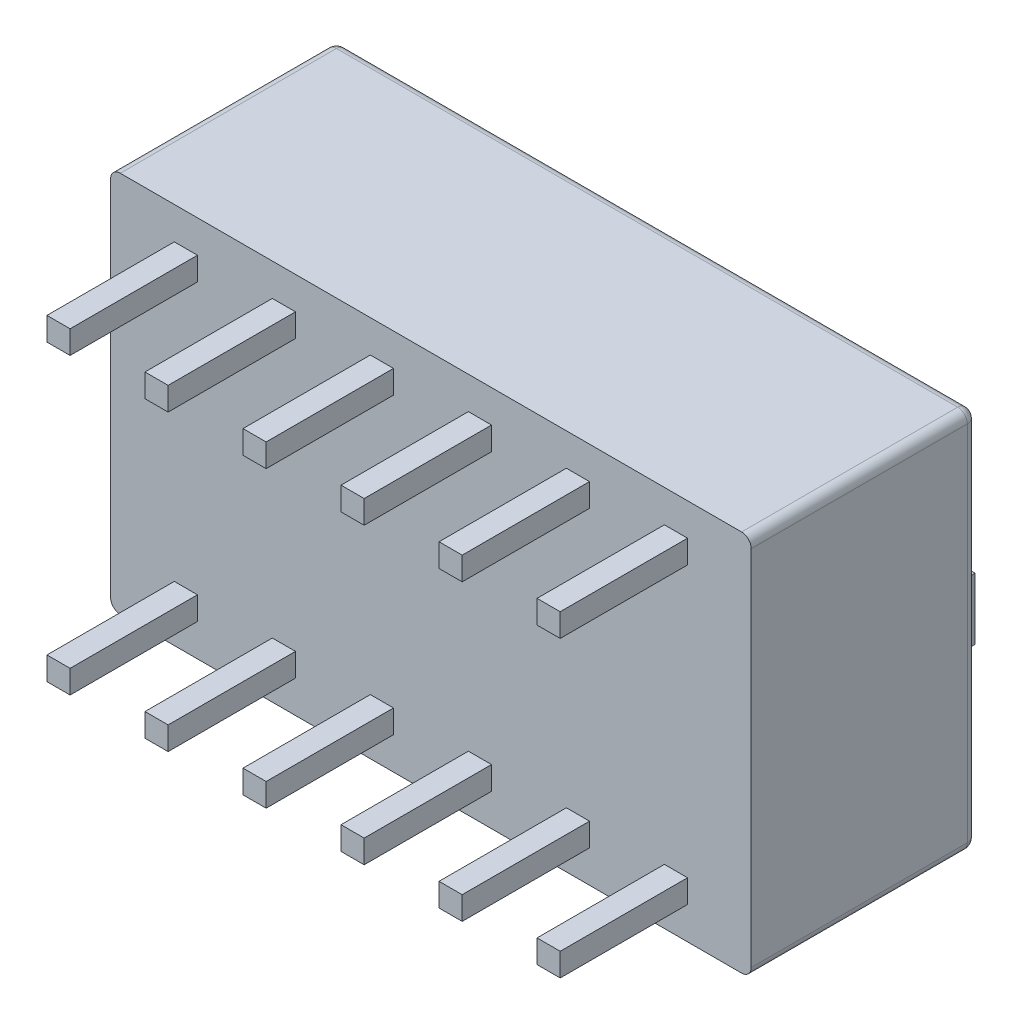
SolidWorks part; units mm, degrees
ref_plane "Ön Düzlem" through (0, 0, 0) normal (0, 0, 1) x (1, 0, 0)
ref_plane "Üst Düzlem" through (0, 0, 0) normal (0, 1, 0) x (1, 0, 0)
ref_plane "Sağ Düzlem" through (0, 0, 0) normal (1, 0, 0) x (0, 0, -1)
sketch "Çizim1" plane through (0, 0, 0) normal (0, 0, 1) x (1, 0, 0)
  line L1 (-8.3, 4.95) -> (8.3, 4.95)
  line L2 (-8.3, 4.95) -> (-8.3, -4.95)
  line L3 (-8.3, -4.95) -> (8.3, -4.95)
  line L4 (8.3, 4.95) -> (8.3, -4.95)
  line L5 (-8.3, 4.95) -> (8.3, -4.95) construction
  line L6 (-8.3, -4.95) -> (8.3, 4.95) construction
  point P0 (0, 0)
extrude "Yükseklik-Ekstrüzyon1" add sketch "Çizim1" along normal blind 5.85
sketch "Çizim2" plane through (0, 0, 0) normal (0, 0, -1) x (-1, 0, 0)
  line L10 (-7.05, 1.6) -> (-5.65, 1.6)
  line L11 (-7.05, 1.6) -> (-7.05, -1.6)
  line L12 (-7.05, -1.6) -> (-5.65, -1.6)
  line L13 (-5.65, 1.6) -> (-5.65, -1.6)
  line L14 (-7.05, 1.6) -> (-5.65, -1.6) construction
  line L15 (-7.05, -1.6) -> (-5.65, 1.6) construction
  line L16 (-4.51, 1.6) -> (-3.11, 1.6)
  line L17 (-4.51, 1.6) -> (-4.51, -1.6)
  line L18 (-4.51, -1.6) -> (-3.11, -1.6)
  line L19 (-3.11, 1.6) -> (-3.11, -1.6)
  line L20 (-4.51, 1.6) -> (-3.11, -1.6) construction
  line L21 (-4.51, -1.6) -> (-3.11, 1.6) construction
  line L22 (-1.97, 1.6) -> (-0.57, 1.6)
  line L23 (-1.97, 1.6) -> (-1.97, -1.6)
  line L24 (-1.97, -1.6) -> (-0.57, -1.6)
  line L25 (-0.57, 1.6) -> (-0.57, -1.6)
  line L26 (-1.97, 1.6) -> (-0.57, -1.6) construction
  line L27 (-1.97, -1.6) -> (-0.57, 1.6) construction
  line L28 (0.57, 1.6) -> (1.97, 1.6)
  line L29 (0.57, 1.6) -> (0.57, -1.6)
  line L30 (0.57, -1.6) -> (1.97, -1.6)
  line L31 (1.97, 1.6) -> (1.97, -1.6)
  line L32 (0.57, 1.6) -> (1.97, -1.6) construction
  line L33 (0.57, -1.6) -> (1.97, 1.6) construction
  line L34 (3.11, 1.6) -> (4.51, 1.6)
  line L35 (3.11, 1.6) -> (3.11, -1.6)
  line L36 (3.11, -1.6) -> (4.51, -1.6)
  line L37 (4.51, 1.6) -> (4.51, -1.6)
  line L38 (3.11, 1.6) -> (4.51, -1.6) construction
  line L39 (3.11, -1.6) -> (4.51, 1.6) construction
  line L40 (7.05, 1.6) -> (5.65, 1.6)
  line L41 (7.05, 1.6) -> (7.05, -1.6)
  line L42 (7.05, -1.6) -> (5.65, -1.6)
  line L43 (5.65, 1.6) -> (5.65, -1.6)
  line L44 (7.05, 1.6) -> (5.65, -1.6) construction
  line L45 (7.05, -1.6) -> (5.65, 1.6) construction
extrude "Kes-Ekstrüzyon1" cut sketch "Çizim2" against normal blind 1
sketch "Çizim3" plane through (0, 0, 1) normal (0, 0, -1) x (-1, 0, 0)
  line L0 (-5.65, -1.6) -> (-5.65, 1.6) construction
  line L1 (-7.05, -1.6) -> (-5.65, -1.6)
  line L2 (-7.05, -1.6) -> (-7.05, 0)
  line L3 (-7.05, 0) -> (-5.65, 0)
  line L4 (-5.65, -1.6) -> (-5.65, 0)
  line L5 (-4.51, 1.6) -> (-4.51, -1.6) construction
  line L6 (-4.51, 0) -> (-3.11, 0)
  line L7 (-4.51, 0) -> (-4.51, -1.6)
  line L8 (-4.51, -1.6) -> (-3.11, -1.6)
  line L9 (-3.11, 0) -> (-3.11, -1.6)
  line L10 (-0.57, -1.6) -> (-0.57, 1.6) construction
  line L11 (-1.97, -1.6) -> (-0.57, -1.6)
  line L12 (-1.97, -1.6) -> (-1.97, 0)
  line L13 (-1.97, 0) -> (-0.57, 0)
  line L14 (-0.57, -1.6) -> (-0.57, 0)
  line L15 (0.57, 1.6) -> (0.57, -1.6) construction
  line L16 (0.57, 0) -> (1.97, 0)
  line L17 (0.57, 0) -> (0.57, -1.6)
  line L18 (0.57, -1.6) -> (1.97, -1.6)
  line L19 (1.97, 0) -> (1.97, -1.6)
  line L20 (4.51, -1.6) -> (4.51, 1.6) construction
  line L21 (3.11, -1.6) -> (4.51, -1.6)
  line L22 (3.11, -1.6) -> (3.11, 0)
  line L23 (3.11, 0) -> (4.51, 0)
  line L24 (4.51, -1.6) -> (4.51, 0)
  line L25 (5.65, 1.6) -> (5.65, -1.6) construction
  line L26 (5.65, 0) -> (7.05, 0)
  line L27 (5.65, 0) -> (5.65, -1.6)
  line L28 (5.65, -1.6) -> (7.05, -1.6)
  line L29 (7.05, 0) -> (7.05, -1.6)
extrude "Yükseklik-Ekstrüzyon2" add sketch "Çizim3" along normal blind 2.2 separate body
sketch "Çizim4" plane through (0, 0, 1) normal (0, 0, -1) x (-1, 0, 0)
  line L0 (-5.65, -1.6) -> (-5.65, 1.6) construction
  line L1 (-7.05, 1.6) -> (-5.65, 1.6)
  line L2 (-7.05, 1.6) -> (-7.05, 0)
  line L3 (-7.05, 0) -> (-5.65, 0)
  line L4 (-5.65, 1.6) -> (-5.65, 0)
  line L5 (-3.11, -1.6) -> (-3.11, 1.6) construction
  line L6 (-4.51, 1.6) -> (-3.11, 1.6)
  line L7 (-4.51, 1.6) -> (-4.51, 0)
  line L8 (-4.51, 0) -> (-3.11, 0)
  line L9 (-3.11, 1.6) -> (-3.11, 0)
  line L10 (-0.57, -1.6) -> (-0.57, 1.6) construction
  line L11 (-1.97, 1.6) -> (-0.57, 1.6)
  line L12 (-1.97, 1.6) -> (-1.97, 0)
  line L13 (-1.97, 0) -> (-0.57, 0)
  line L14 (-0.57, 1.6) -> (-0.57, 0)
  line L15 (4.51, -1.6) -> (4.51, 1.6) construction
  line L16 (0.57, 1.6) -> (1.97, 1.6)
  line L17 (0.57, 1.6) -> (0.57, 0)
  line L18 (0.57, 0) -> (1.97, 0)
  line L19 (1.97, 1.6) -> (1.97, 0)
  line L20 (3.11, 1.6) -> (4.51, 1.6)
  line L21 (3.11, 1.6) -> (3.11, 0)
  line L22 (3.11, 0) -> (4.51, 0)
  line L23 (4.51, 1.6) -> (4.51, 0)
  line L24 (7.05, -1.6) -> (7.05, 1.6) construction
  line L25 (5.65, 1.6) -> (7.05, 1.6)
  line L26 (5.65, 1.6) -> (5.65, 0)
  line L27 (5.65, 0) -> (7.05, 0)
  line L28 (7.05, 1.6) -> (7.05, 0)
extrude "Yükseklik-Ekstrüzyon3" add sketch "Çizim4" along normal blind 0.9 separate body
fillet "Radyus1" radius 0.25 8 edges at (0, -4.95, 0) (8.3, 0, 0) (8.3, -4.95, 2.925) (8.3, 4.95, 2.925) (-8.3, -4.95, 2.925) (0, 4.95, 0) (-8.3, 4.95, 2.925) (-8.3, 0, 0)
sketch "Çizim5" plane through (0, 0, 5.85) normal (0, 0, 1) x (1, 0, 0)
  line L14 (-6.65, -4.11) -> (-6.05, -4.11)
  line L15 (-6.65, -4.11) -> (-6.65, -3.51)
  line L16 (-6.65, -3.51) -> (-6.05, -3.51)
  line L17 (-6.05, -4.11) -> (-6.05, -3.51)
  line L18 (-6.65, -4.11) -> (-6.05, -3.51) construction
  line L19 (-6.65, -3.51) -> (-6.05, -4.11) construction
  line L20 (-4.11, -4.11) -> (-3.51, -4.11)
  line L21 (-4.11, -4.11) -> (-4.11, -3.51)
  line L22 (-4.11, -3.51) -> (-3.51, -3.51)
  line L23 (-3.51, -4.11) -> (-3.51, -3.51)
  line L24 (-4.11, -4.11) -> (-3.51, -3.51) construction
  line L25 (-4.11, -3.51) -> (-3.51, -4.11) construction
  line L26 (-1.57, -4.11) -> (-0.97, -4.11)
  line L27 (-1.57, -4.11) -> (-1.57, -3.51)
  line L28 (-1.57, -3.51) -> (-0.97, -3.51)
  line L29 (-0.97, -4.11) -> (-0.97, -3.51)
  line L30 (-1.57, -4.11) -> (-0.97, -3.51) construction
  line L31 (-1.57, -3.51) -> (-0.97, -4.11) construction
  line L32 (0.97, -4.11) -> (1.57, -4.11)
  line L33 (0.97, -4.11) -> (0.97, -3.51)
  line L34 (0.97, -3.51) -> (1.57, -3.51)
  line L35 (1.57, -4.11) -> (1.57, -3.51)
  line L36 (0.97, -4.11) -> (1.57, -3.51) construction
  line L37 (0.97, -3.51) -> (1.57, -4.11) construction
  line L38 (3.51, -4.11) -> (4.11, -4.11)
  line L39 (3.51, -4.11) -> (3.51, -3.51)
  line L40 (3.51, -3.51) -> (4.11, -3.51)
  line L41 (4.11, -4.11) -> (4.11, -3.51)
  line L42 (3.51, -4.11) -> (4.11, -3.51) construction
  line L43 (3.51, -3.51) -> (4.11, -4.11) construction
  line L44 (6.05, -4.11) -> (6.65, -4.11)
  line L45 (6.05, -4.11) -> (6.05, -3.51)
  line L46 (6.05, -3.51) -> (6.65, -3.51)
  line L47 (6.65, -4.11) -> (6.65, -3.51)
  line L48 (6.05, -4.11) -> (6.65, -3.51) construction
  line L49 (6.05, -3.51) -> (6.65, -4.11) construction
  line L50 (-6.65, 3.51) -> (-6.05, 3.51)
  line L51 (-6.65, 3.51) -> (-6.65, 4.11)
  line L52 (-6.65, 4.11) -> (-6.05, 4.11)
  line L53 (-6.05, 3.51) -> (-6.05, 4.11)
  line L54 (-6.65, 3.51) -> (-6.05, 4.11) construction
  line L55 (-6.65, 4.11) -> (-6.05, 3.51) construction
  line L56 (-4.11, 3.51) -> (-3.51, 3.51)
  line L57 (-4.11, 3.51) -> (-4.11, 4.11)
  line L58 (-4.11, 4.11) -> (-3.51, 4.11)
  line L59 (-3.51, 3.51) -> (-3.51, 4.11)
  line L60 (-4.11, 3.51) -> (-3.51, 4.11) construction
  line L61 (-4.11, 4.11) -> (-3.51, 3.51) construction
  line L62 (-1.57, 3.51) -> (-0.97, 3.51)
  line L63 (-1.57, 3.51) -> (-1.57, 4.11)
  line L64 (-1.57, 4.11) -> (-0.97, 4.11)
  line L65 (-0.97, 3.51) -> (-0.97, 4.11)
  line L66 (-1.57, 3.51) -> (-0.97, 4.11) construction
  line L67 (-1.57, 4.11) -> (-0.97, 3.51) construction
  line L68 (0.97, 3.51) -> (1.57, 3.51)
  line L69 (0.97, 3.51) -> (0.97, 4.11)
  line L70 (0.97, 4.11) -> (1.57, 4.11)
  line L71 (1.57, 3.51) -> (1.57, 4.11)
  line L72 (0.97, 3.51) -> (1.57, 4.11) construction
  line L73 (0.97, 4.11) -> (1.57, 3.51) construction
  line L74 (3.51, 3.51) -> (4.11, 3.51)
  line L75 (3.51, 3.51) -> (3.51, 4.11)
  line L76 (3.51, 4.11) -> (4.11, 4.11)
  line L77 (4.11, 3.51) -> (4.11, 4.11)
  line L78 (3.51, 3.51) -> (4.11, 4.11) construction
  line L79 (3.51, 4.11) -> (4.11, 3.51) construction
  line L80 (6.05, 3.51) -> (6.65, 3.51)
  line L81 (6.05, 3.51) -> (6.05, 4.11)
  line L82 (6.05, 4.11) -> (6.65, 4.11)
  line L83 (6.65, 3.51) -> (6.65, 4.11)
  line L84 (6.05, 3.51) -> (6.65, 4.11) construction
  line L85 (6.05, 4.11) -> (6.65, 3.51) construction
extrude "Yükseklik-Ekstrüzyon4" add sketch "Çizim5" along normal blind 3.3
